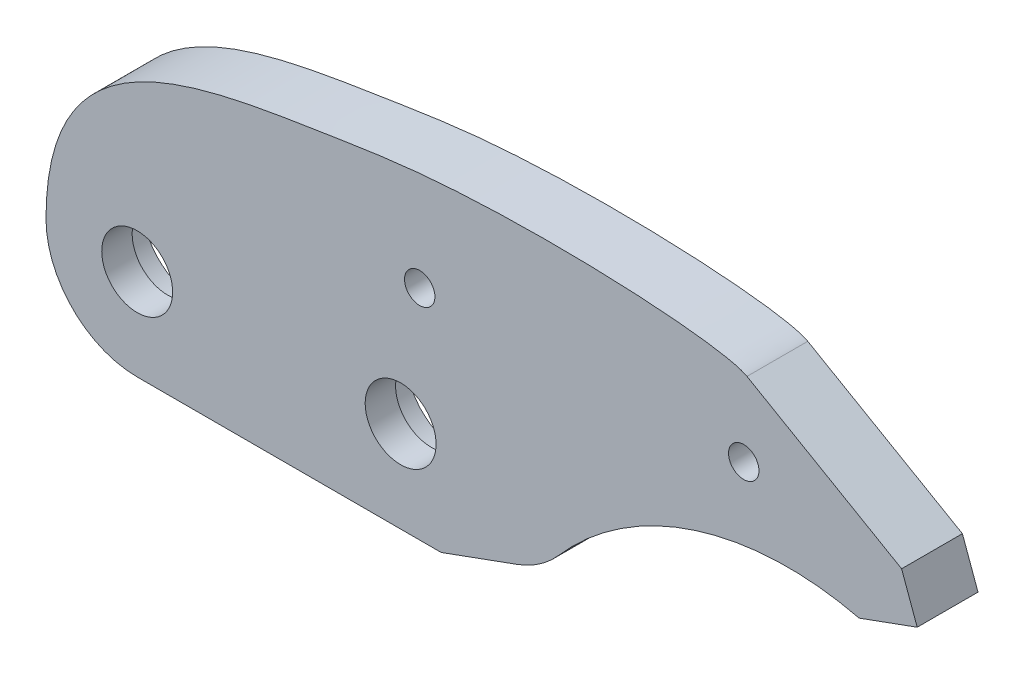
SolidWorks part; units mm, degrees
material "Acrylic (Medium-high impact)"
ref_plane "Front Plane" through (0, 0, 0) normal (0, 0, 1) x (1, 0, 0)
ref_plane "Top Plane" through (0, 0, 0) normal (0, 1, 0) x (1, 0, 0)
ref_plane "Right Plane" through (0, 0, 0) normal (1, 0, 0) x (0, 0, -1)
ref_plane "Plane1"
sketch "Sketch1" plane through (0, 0, 0) normal (0, 0, 1) x (1, 0, 0)
  line L0 (0, -9) -> (30, -9)
  line L3 (30, -9) -> (76.9846, 8.101)
  line L4 (26.8261, 9) -> (32.9825, -7.9145) construction
  line L5 (0, -9) -> (0, 9) construction
  line L14 (76.9846, 8.101) -> (75.4455, 12.3296)
  line L15 (75.4455, 12.3296) -> (60.1836, 21.1411)
  line L16 (60.1836, 21.1411) -> (26.8261, 9)
  line L17 (26.8261, 9) -> (0, 9)
  line L18 (0, 0) -> (26, 0) construction
  arc A0 (0, 9) -> (0, -9) centre (0, 0) ccw
  circle A1 centre (0, 0) radius 3.5
  circle A2 centre (26, 0) radius 3.5
  dimension "D7" = 7
  dimension "D1" = 18
  dimension "D2" = 160
  dimension "D3" = 140
  dimension "D4" = 50
  dimension "D5" = 4.5
  dimension "D6" = 30
  dimension "D11" = 26
extrude "Extrusion1" add sketch "Sketch1" along normal blind 6
ref_plane "Plane3"
sketch "Sketch3" plane through (0, 0, 0) normal (0, 0, -1) x (-1, 0, 0)
  line L0 (-53.9617, 5.0423) -> (-55.6718, 0.3438) construction
  line L1 (-30, -9) -> (-76.9846, 8.101) construction
  line L2 (-64.2224, -23.1485) -> (-55.6718, 0.3438) construction
  circle A0 centre (-64.2224, -23.1485) radius 30
  point P2 (-53.9617, 5.0423)
  dimension "D1" = 60
  dimension "D2" = 5
  dimension "D3" = 28
extrude "Extrusion3" cut sketch "Sketch3" against normal blind 10
sketch "Sketch5" plane through (0, 0, 0) normal (0, 0, -1) x (-1, 0, 0)
  line L0 (-61.2126, -14.8792) -> (-52.7246, 8.4412) construction
  line L1 (-30, -9) -> (-76.9846, 8.101) construction
  circle A0 centre (-61.3407, -15.2313) radius 25
  arc A1 (-40.0888, -5.328) -> (-71.2549, 6.0156) centre (-64.2224, -23.1485) ccw construction
  point P6 (-53.9617, 5.0423)
  dimension "D1" = 50
fillet "Fillet2" radius 10 1 edges at (40.0888, -5.328, 3)
sketch "Sketch6" plane through (0, 0, 0) normal (0, 0, -1) x (-1, 0, 0)
  line L0 (9, 0) -> (9, -7.9217) construction
  line L7 (-37.4748, -6.2794) -> (-30, -9)
  line L8 (-30, -9) -> (0, -9)
  line L9 (0, 9) -> (-26.8261, 9)
  line L10 (-26.8261, 9) -> (-60.1836, 21.1411)
  line L11 (-60.1836, 21.1411) -> (-75.4455, 12.3296)
  line L12 (-75.4455, 12.3296) -> (-76.9846, 8.101)
  line L13 (-76.9846, 8.101) -> (-71.2549, 6.0156)
  line L14 (-37.4748, -6.2794) -> (-30, -9)
  line L15 (-30, -9) -> (0, -9)
  line L16 (0, 9) -> (-26.8261, 9)
  line L17 (-26.8261, 9) -> (-60.1836, 21.1411)
  line L18 (-60.1836, 21.1411) -> (-75.4455, 12.3296)
  line L19 (-75.4455, 12.3296) -> (-76.9846, 8.101)
  line L20 (-76.9846, 8.101) -> (-71.2549, 6.0156)
  arc A3 (-41.5965, -3.449) -> (-71.2549, 6.0156) centre (-64.2224, -23.1485) ccw
  arc A4 (-41.5965, -3.449) -> (-37.4748, -6.2794) centre (-34.0546, 3.1175) ccw
  arc A5 (0, -9) -> (0, 9) centre (0, 0) ccw
  arc A6 (-41.5965, -3.449) -> (-71.2549, 6.0156) centre (-64.2224, -23.1485) ccw
  arc A7 (-41.5965, -3.449) -> (-37.4748, -6.2794) centre (-34.0546, 3.1175) ccw
  arc A8 (0, -9) -> (0, 9) centre (0, 0) ccw
  spline S0 degree 3 poles (-60.1836, 21.1411) (-57.583, 22.6426) (-35.7854, 23.8386) (-8.3771, 19.44) (9, 16.914) (9, 0) knots 0 0 0 0 0.435384 0.535384 1 1 1 1
  line M19 (0, 9) -> (-26.8261, 9)
  line M20 (-26.8261, 9) -> (-60.1836, 21.1411)
  dimension "D1" = 0
extrude "Boss-Extrude1" add sketch "Sketch6" against normal up to surface (6 mm away) contours S0 A8 M20 M19 up to face at (40.9622, 4.1745, 6)
sketch "Sketch7" plane through (0, 0, 0) normal (0, 0, -1) x (-1, 0, 0)
  circle A0 centre (0, 0) radius 5.5
  circle A1 centre (-26, 0) radius 5.5
  dimension "D1" = 11
sketch "Sketch8" plane through (0, 0, 0) normal (0, 0, -1) x (-1, 0, 0)
  line L0 (-76.9846, 8.101) -> (-59.8656, 13.6633) construction
  line L1 (-75.4455, 12.3296) -> (-60.1836, 21.1411) construction
  line L2 (-59.8656, 13.6633) -> (-27.8851, 12.5465) construction
  circle A0 centre (-59.8656, 13.6633) radius 1.5
  circle A1 centre (-27.8851, 12.5465) radius 1.5
  dimension "D3" = 3
  dimension "D5" = 160
  dimension "D1" = 12
  dimension "D2" = 18
  dimension "D4" = 32
extrude "Cut-Extrude1" cut sketch "Sketch8" against normal blind 14
extrude "Cut-Extrude2" cut sketch "Sketch7" against normal blind 3
